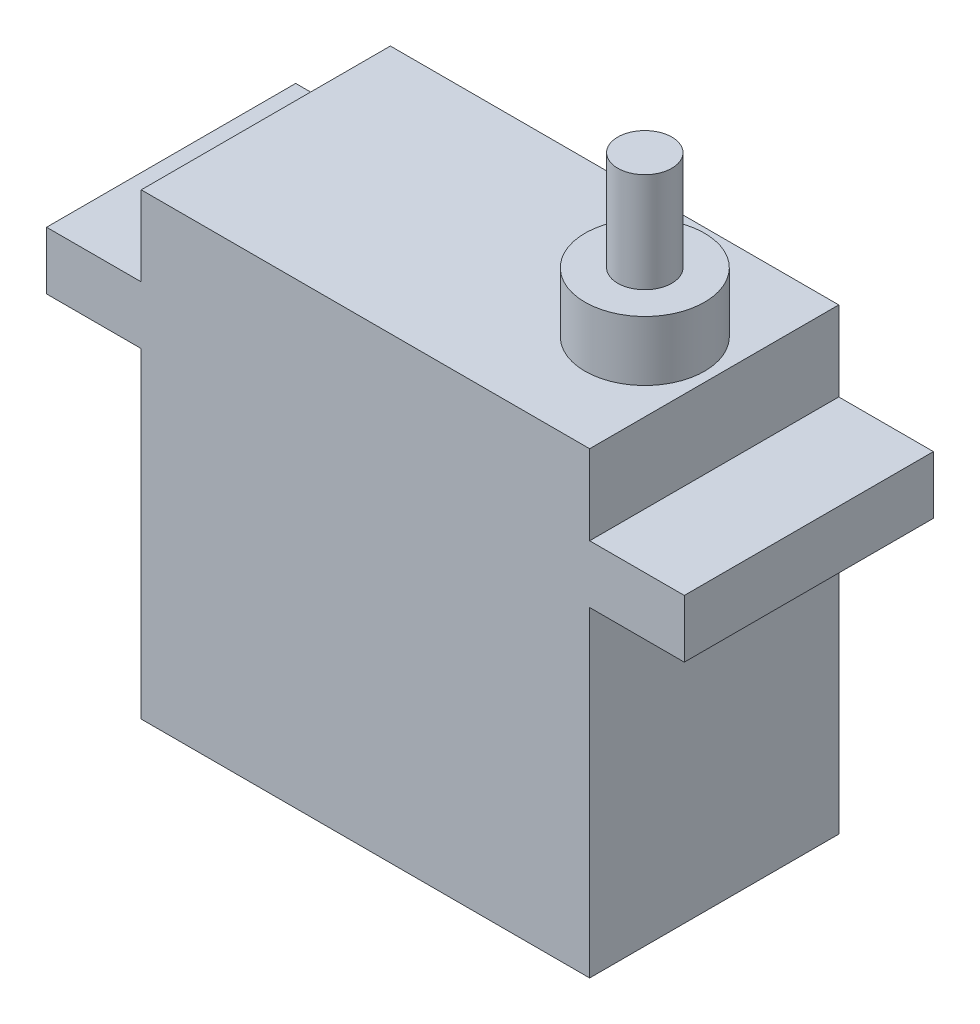
SolidWorks part; units mm, degrees
ref_plane "前视基准面" through (0, 0, 0) normal (0, 0, 1) x (1, 0, 0)
ref_plane "上视基准面" through (0, 0, 0) normal (0, 1, 0) x (1, 0, 0)
ref_plane "右视基准面" through (0, 0, 0) normal (1, 0, 0) x (0, 0, -1)
sketch "草图1" plane through (0, 0, 0) normal (0, 1, 0) x (1, 0, 0)
  line L1 (-16, -6.25) -> (16, -6.25)
  line L2 (-16, -6.25) -> (-16, 6.25)
  line L3 (-16, 6.25) -> (16, 6.25)
  line L4 (16, -6.25) -> (16, 6.25)
  line L5 (-16, -6.25) -> (16, 6.25) construction
  line L6 (-16, 6.25) -> (16, -6.25) construction
  point P0 (0, 0)
  dimension "D1" = 12.5
  dimension "D2" = 32
extrude "凸台-拉伸1" add sketch "草图1" along normal blind 23 contours L4 L3 L2 L1
sketch "草图3" plane through (0, 23, 0) normal (0, 1, 0) x (1, 0, 0)
  line L0 (-16, 6.25) -> (16, 6.25) construction
  line L2 (-11.25, 6.25) -> (-11.25, -6.25)
  line L4 (11.25, 6.25) -> (11.25, -6.25)
  line L5 (-16, -6.25) -> (16, -6.25) construction
  line L8 (-16, 6.25) -> (16, 6.25)
  line L9 (-16, 6.25) -> (-16, -6.25)
  line L10 (-16, -6.25) -> (16, -6.25)
  line L11 (16, 6.25) -> (16, -6.25)
  line M3 (-16, -6.25) -> (16, -6.25)
  line M4 (16, -6.25) -> (16, 6.25)
  line M5 (16, 6.25) -> (-16, 6.25)
  line M6 (-16, 6.25) -> (-16, -6.25)
  dimension "D1" = 22.5
extrude "切除-拉伸2" cut sketch "草图3" against normal blind 4 contours L2 M5 M6 M3 | L4 M5 M3 M4
sketch "草图8" plane through (0, 0, 0) normal (0, -1, 0) x (1, 0, 0)
  line L0 (11.25, -6.25) -> (16, -6.25)
  line L1 (-11.25, 6.25) -> (-16, 6.25)
  line L4 (16, 6.25) -> (-16, 6.25)
  line L5 (-16, 6.25) -> (-16, -6.25)
  line L6 (-16, -6.25) -> (16, -6.25)
  line L7 (16, -6.25) -> (16, 6.25)
  line L8 (16, 6.25) -> (11.25, 6.25)
  line L9 (-16, 6.25) -> (-16, -6.25)
  line L10 (-16, -6.25) -> (-11.25, -6.25)
  line L11 (16, -6.25) -> (16, 6.25)
  line L12 (11.25, -6.25) -> (16, -6.25)
  line L13 (11.25, 6.25) -> (11.25, -6.25)
  line L14 (16, 6.25) -> (11.25, 6.25)
  line L15 (16, -6.25) -> (16, 6.25)
  line L16 (11.25, -6.25) -> (16, -6.25)
  line L17 (11.25, 6.25) -> (11.25, -6.25)
  line L18 (16, 6.25) -> (11.25, 6.25)
  line L19 (16, -6.25) -> (16, 6.25)
  line L20 (-11.25, -6.25) -> (-11.25, 6.25)
  line L21 (-16, -6.25) -> (-11.25, -6.25)
  line L22 (-16, 6.25) -> (-16, -6.25)
  line L23 (-11.25, 6.25) -> (-16, 6.25)
  line L24 (-11.25, -6.25) -> (-11.25, 6.25)
  line L25 (-16, -6.25) -> (-11.25, -6.25)
  line L26 (-16, 6.25) -> (-16, -6.25)
  line L27 (-11.25, 6.25) -> (-16, 6.25)
  line M13 (16, 6.25) -> (-16, 6.25)
  line M14 (-16, 6.25) -> (-16, -6.25)
  line M15 (-16, -6.25) -> (16, -6.25)
  line M16 (16, -6.25) -> (16, 6.25)
  dimension "D1" = 0
  dimension "D2" = 0
  dimension "D3" = 0
extrude "切除-拉伸3" cut sketch "草图8" against normal blind 16.1 contours L17 M13 M15 M16 | L24 M15 M13 M14
sketch "草图9" plane through (0, 23, 0) normal (0, 1, 0) x (1, 0, 0)
  circle A0 centre (7.767, 0) radius 3
  dimension "D1" = 6
extrude "凸台-拉伸2" add sketch "草图9" along normal blind 3
sketch "草图10" plane through (0, 26, 0) normal (0, 1, 0) x (1, 0, 0)
  circle A0 centre (7.767, 0) radius 1.3568
extrude "凸台-拉伸3" add sketch "草图10" along normal blind 5
